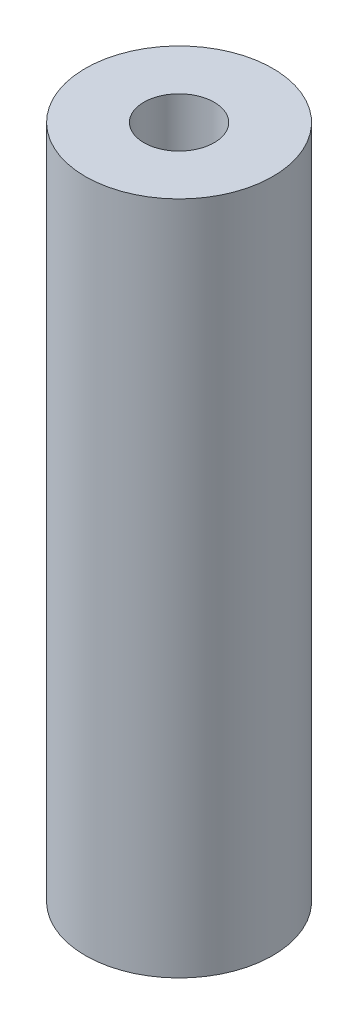
SolidWorks part; units mm, degrees
ref_plane "Front Plane" through (0, 0, 0) normal (0, 0, 1) x (1, 0, 0)
ref_plane "Top Plane" through (0, 0, 0) normal (0, 1, 0) x (1, 0, 0)
ref_plane "Right Plane" through (0, 0, 0) normal (1, 0, 0) x (0, 0, -1)
sketch "Sketch1" plane through (0, 0, 0) normal (0, 1, 0) x (1, 0, 0)
  circle A0 centre (0, 0) radius 1.5
  circle A1 centre (0, 0) radius 4
  dimension "D1" = 8
  dimension "D2" = 3
extrude "Boss-Extrude1" add sketch "Sketch1" along normal blind 28.8
